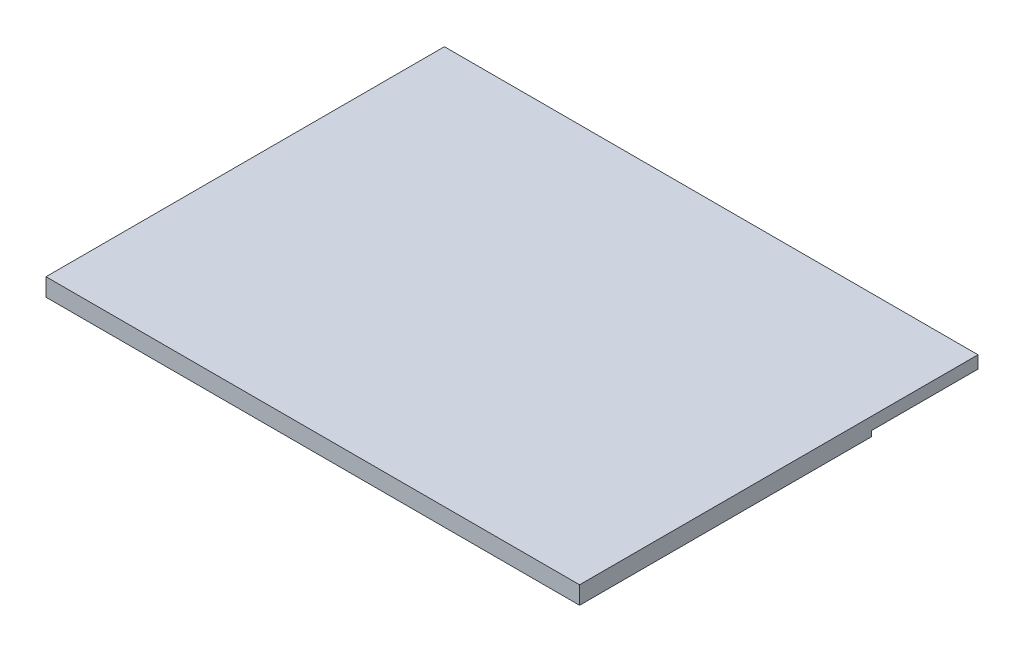
SolidWorks part; units mm, degrees
ref_plane "Front Plane" through (0, 0, 0) normal (0, 0, 1) x (1, 0, 0)
ref_plane "Top Plane" through (0, 0, 0) normal (0, 1, 0) x (1, 0, 0)
ref_plane "Right Plane" through (0, 0, 0) normal (1, 0, 0) x (0, 0, -1)
sketch "Sketch1" plane through (0, 0, 0) normal (0, 1, 0) x (1, 0, 0)
  line L1 (-2.5, 56) -> (2.5, 56)
  line L2 (-2.5, 56) -> (-2.5, -56)
  line L3 (-2.5, -56) -> (2.5, -56)
  line L4 (2.5, 56) -> (2.5, -56)
  line L5 (-2.5, 56) -> (2.5, -56) construction
  line L6 (-2.5, -56) -> (2.5, 56) construction
  point P0 (0, 0)
  dimension "D1" = 112
  dimension "D2" = 5
extrude "Boss-Extrude1" add sketch "Sketch1" along normal blind 5
sketch "Sketch2" plane through (2.5, 0, 0) normal (1, 0, 0) x (0, 0, -1)
  line L1 (56, 5) -> (-56, 5)
  line L2 (56, 5) -> (56, 0)
  line L3 (56, 0) -> (-56, 0)
  line L4 (-56, 5) -> (-56, 0)
extrude "Boss-Extrude2" add sketch "Sketch2" along normal up to surface (145 mm away)
sketch "Sketch3" plane through (0, 0, -56) normal (0, 0, -1) x (-1, 0, 0)
  line L0 (-136.6515, 0) -> (-141.2515, -4.6)
  line L1 (-147.5, 0) -> (2.5, 0) construction
  line L2 (-141.2515, -4.6) -> (-3.7485, -4.6)
  line L3 (-3.7485, -4.6) -> (-8.3485, 0)
  line L4 (-137.5, 0) -> (-142.5, -5) construction
  line L5 (-2.5, -5) -> (-7.5, 0) construction
  line L6 (-142.5, -5) -> (-97.5, -5) construction
  line L7 (-136.6515, 0) -> (-8.3485, 0)
  dimension "D1" = 0.6
  dimension "D2" = 0.4
  dimension "D3" = 0.6
extrude "Boss-Extrude3" add sketch "Sketch3" against normal up to surface (107 mm away)
sketch "Sketch5" plane through (0, 0, -56) normal (0, 0, -1) x (-1, 0, 0)
  line L0 (-147.5, 5) -> (-147.5, 0) construction
  line L1 (-147.5, 1.5) -> (2.5, 1.5)
  line L2 (-147.5, 1.5) -> (-147.5, -1.5)
  line L3 (-147.5, -1.5) -> (2.5, -1.5)
  line L4 (2.5, 1.5) -> (2.5, -1.5)
  line L5 (2.5, 5) -> (2.5, 0) construction
  dimension "D1" = 3
extrude "Cut-Extrude1" cut sketch "Sketch5" against normal blind 30
chamfer "Chamfer1" distance 2 angle 45 2 edges at (3.7485, -4.6, -2.5) (141.2515, -4.6, -2.5)
sketch "Sketch6" plane through (0, -4.6, 0) normal (0, -1, 0) x (1, 0, 0)
  line L1 (6.8485, -50.8) -> (138.1515, -50.8)
  line L2 (6.8485, -50.8) -> (6.8485, -35.8)
  line L3 (6.8485, -35.8) -> (138.1515, -35.8)
  line L4 (138.1515, -50.8) -> (138.1515, -35.8)
  line L9 (6.8485, -56) -> (6.8485, -26) construction
  line L10 (138.1515, -26) -> (138.1515, -56) construction
  line L11 (139.2515, -56) -> (5.7485, -56) construction
  dimension "D1" = 15
  dimension "D2" = 5.2
extrude "Boss-Extrude4" add sketch "Sketch6" along normal blind 2
sketch "Sketch7" plane through (138.1515, 0, 0) normal (1, 0, 0) x (0, 0, -1)
  line L0 (35.8, -4.6) -> (52.8358, -6.6)
  line L1 (50.8, -6.6) -> (35.8, -6.6) construction
  line L2 (35.8, -4.6) -> (35.8, -6.6)
  line L3 (35.8, -6.6) -> (52.8358, -6.6)
extrude "Cut-Extrude2" cut sketch "Sketch7" against normal up to surface (131.3029 mm away) up to face at (6.8485, -5.6, -43.3)
